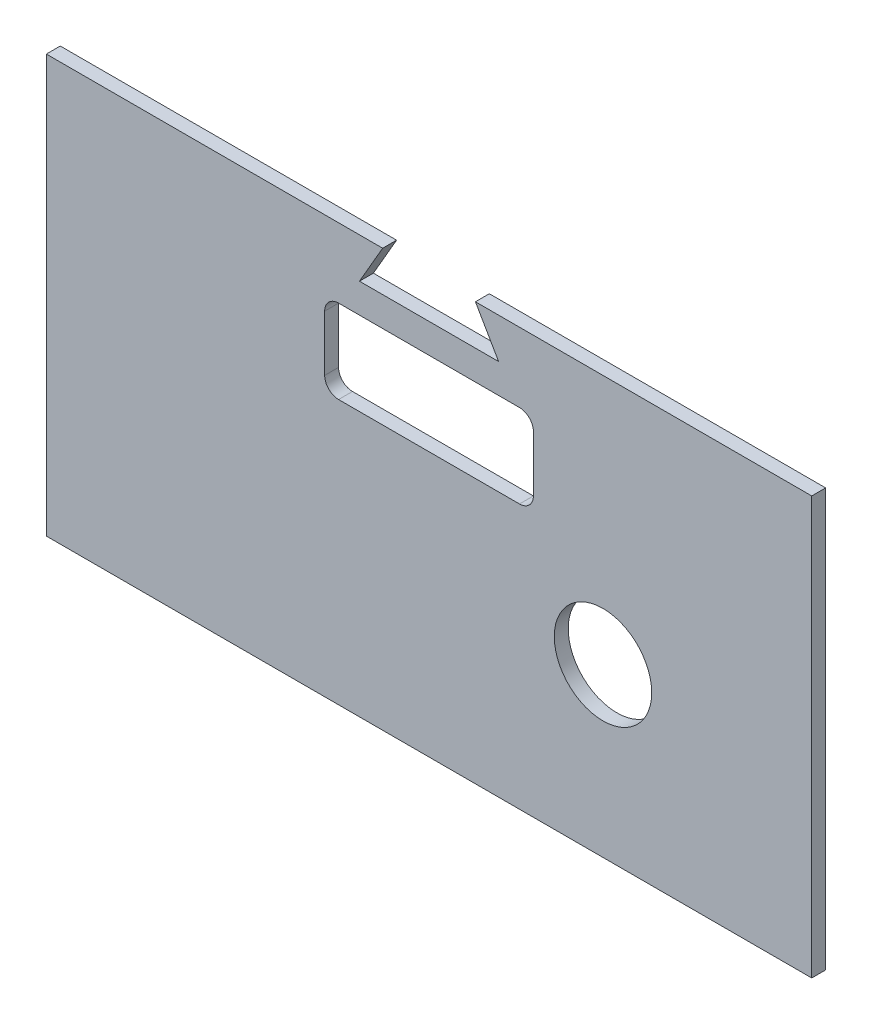
SolidWorks part; units mm, degrees
ref_plane "Front Plane" through (0, 0, 0) normal (0, 0, 1) x (1, 0, 0)
ref_plane "Top Plane" through (0, 0, 0) normal (0, 1, 0) x (1, 0, 0)
ref_plane "Right Plane" through (0, 0, 0) normal (1, 0, 0) x (0, 0, -1)
sketch "Sketch1" plane through (0, 0, 0) normal (0, 0, 1) x (1, 0, 0)
  line L1 (-27.5, -15) -> (27.5, -15)
  line L2 (-27.5, -15) -> (-27.5, 15)
  line L3 (-27.5, 15) -> (27.5, 15)
  line L4 (27.5, -15) -> (27.5, 15)
  line L5 (-27.5, -15) -> (27.5, 15) construction
  line L6 (-27.5, 15) -> (27.5, -15) construction
  point P0 (0, 0)
  dimension "D1" = 55
  dimension "D2" = 30
extrude "Boss-Extrude1" add sketch "Sketch1" along normal blind 1
sketch "Sketch2" plane through (0, 0, 1) normal (0, 0, 1) x (1, 0, 0)
  line L0 (27.5, -15) -> (27.5, 15) construction
  line L1 (-7.5, 10) -> (7.5, 10)
  line L2 (-7.5, 10) -> (-7.5, 4)
  line L3 (-7.5, 4) -> (7.5, 4)
  line L4 (7.5, 10) -> (7.5, 4)
  line L5 (-27.5, -15) -> (27.5, -15) construction
  line L6 (0, 15) -> (0, -15) construction
  line L7 (27.5, 15) -> (-27.5, 15) construction
  line L9 (0, 20.7735) -> (-5, 12.1132)
  line L10 (-5, 12.1132) -> (5, 12.1132)
  line L11 (5, 12.1132) -> (0, 20.7735)
  circle A0 centre (12.5, -3) radius 3.5
  circle A1 centre (0, 15) radius 2.8868 construction
  dimension "D5" = 7
  dimension "D6" = 12
  dimension "D7" = 15
  dimension "D1" = 15
  dimension "D2" = 6
  dimension "D3" = 35
  dimension "D4" = 25
  dimension "D8" = 10
extrude "Cut-Extrude1" cut sketch "Sketch2" against normal through all both and the other way through all
fillet "Fillet1" radius 1 4 edges at (-7.5, 4, 0.5) (7.5, 4, 0.5) (7.5, 10, 0.5) (-7.5, 10, 0.5)
